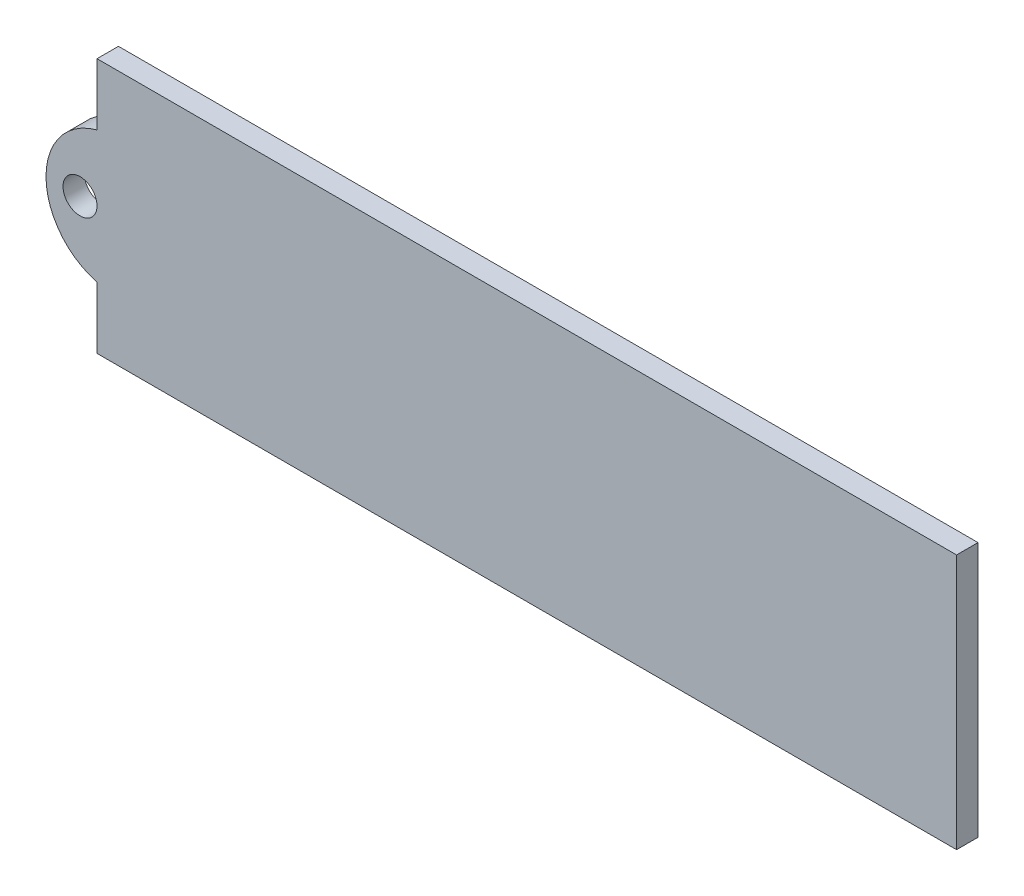
SolidWorks part; units mm, degrees
ref_plane "Front Plane" through (0, 0, 0) normal (0, 0, 1) x (1, 0, 0)
ref_plane "Top Plane" through (0, 0, 0) normal (0, 1, 0) x (1, 0, 0)
ref_plane "Right Plane" through (0, 0, 0) normal (1, 0, 0) x (0, 0, -1)
sketch "Sketch2" plane through (0, 0, 0) normal (0, 0, 1) x (1, 0, 0)
  line L0 (-38.5254, 10.3251) -> (-38.5254, -10.3251)
  line L1 (38.5254, -10.3251) -> (-38.5254, -10.3251)
  line L2 (38.5254, 10.3251) -> (38.5254, -10.3251)
  line L3 (-38.5254, 10.3251) -> (38.5254, 10.3251)
  line L4 (-40.1129, 11.9126) -> (40.1129, 11.9126)
  line L5 (40.1129, 11.9126) -> (40.1129, -11.9126)
  line L6 (40.1129, -11.9126) -> (-40.1129, -11.9126)
  line L7 (-40.1129, 11.9126) -> (-40.1129, -11.9126)
  line L8 (-40.1129, 11.9126) -> (40.1129, -11.9126) construction
  line L9 (40.1129, 11.9126) -> (-40.1129, -11.9126) construction
  line L10 (-38.5254, 10.3251) -> (38.5254, -10.3251) construction
  line L11 (38.5254, 10.3251) -> (-38.5254, -10.3251) construction
  circle A0 centre (-38.5254, 0) radius 6.35
  point P10 (0, 0)
extrude "Boss-Extrude1" add sketch "Sketch2" along normal blind 2 contours L7 A0 | L0 A0 L7 | L0 A0 | A0 L0 L1 L2 L3 | A0 L0 L3 L2 L1 L7 L6 L5 L4
sketch "Sketch5" plane through (0, 0, 0) normal (0, 0, -1) x (-1, 0, 0)
  line L0 (43.5335, 0) -> (42.617, -1.5875) construction
  line L1 (43.5335, 0) -> (42.617, -1.5875)
  line L2 (42.617, 1.5875) -> (43.5335, 0) construction
  line L3 (40.7839, 1.5875) -> (42.617, 1.5875) construction
  line L4 (40.7839, -1.5875) -> (39.8674, 0) construction
  line L5 (40.1129, 6.1484) -> (40.1129, 11.9126)
  line L6 (40.1129, 11.9126) -> (-40.1129, 11.9126)
  line L7 (-40.1129, 11.9126) -> (-40.1129, -11.9126)
  line L8 (-40.1129, -11.9126) -> (40.1129, -11.9126)
  line L9 (40.1129, -11.9126) -> (40.1129, -6.1484)
  line L10 (40.1129, 6.1484) -> (40.1129, 11.9126)
  line L11 (40.1129, 11.9126) -> (-40.1129, 11.9126)
  line L12 (-40.1129, 11.9126) -> (-40.1129, -11.9126)
  line L13 (-40.1129, -11.9126) -> (40.1129, -11.9126)
  line L14 (40.1129, -11.9126) -> (40.1129, -6.1484)
  line L15 (39.8674, 0) -> (40.7839, 1.5875) construction
  line L16 (42.617, -1.5875) -> (40.7839, -1.5875) construction
  line L17 (43.5335, 0) -> (42.617, -1.5875)
  line L18 (42.617, 1.5875) -> (43.5335, 0)
  line L19 (40.7839, 1.5875) -> (42.617, 1.5875)
  line L20 (40.7839, -1.5875) -> (39.8674, 0)
  line L21 (39.8674, 0) -> (40.7839, 1.5875)
  line L22 (42.617, -1.5875) -> (40.7839, -1.5875)
  line L23 (40.7839, 1.5875) -> (42.617, -1.5875) construction
  line L24 (40.7839, -1.5875) -> (42.617, 1.5875) construction
  circle A0 centre (41.7005, 0) radius 1.5875
  arc A1 (40.1129, -6.1484) -> (40.1129, 6.1484) centre (38.5254, 0) ccw
  arc A2 (40.1129, -6.1484) -> (40.1129, 6.1484) centre (38.5254, 0) ccw
  dimension "D1" = 0
extrude "Cut-Extrude1" cut sketch "Sketch5" against normal blind 2.54 contours A0
